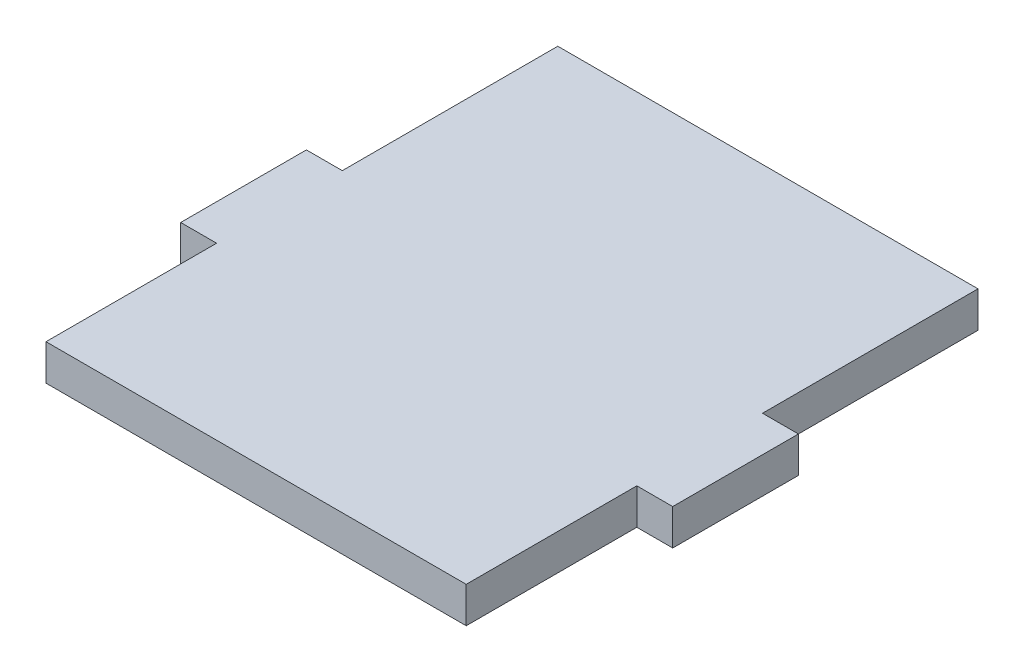
SolidWorks part; units mm, degrees
ref_plane "Front Plane" through (0, 0, 0) normal (0, 0, 1) x (1, 0, 0)
ref_plane "Top Plane" through (0, 0, 0) normal (0, 1, 0) x (1, 0, 0)
ref_plane "Right Plane" through (0, 0, 0) normal (1, 0, 0) x (0, 0, -1)
sketch "Sketch1" plane through (0, 0, 0) normal (0, 1, 0) x (1, 0, 0)
  line L1 (-11.7, 14.25) -> (11.7, 14.25)
  line L2 (-11.7, 14.25) -> (-11.7, -14.25)
  line L3 (-11.7, -14.25) -> (11.7, -14.25)
  line L4 (11.7, 14.25) -> (11.7, -14.25)
  line L5 (-11.7, 14.25) -> (11.7, -14.25) construction
  line L6 (-11.7, -14.25) -> (11.7, 14.25) construction
  line L7 (11.7, -4.75) -> (13.7, -4.75)
  line L8 (11.7, -4.75) -> (11.7, 2.25)
  line L9 (11.7, 2.25) -> (13.7, 2.25)
  line L10 (13.7, -4.75) -> (13.7, 2.25)
  line L11 (-11.7, 2.25) -> (-13.7, 2.25)
  line L12 (-11.7, 2.25) -> (-11.7, -4.75)
  line L13 (-11.7, -4.75) -> (-13.7, -4.75)
  line L14 (-13.7, 2.25) -> (-13.7, -4.75)
  point P0 (0, 0)
  dimension "D1" = 28.5
  dimension "D2" = 23.4
  dimension "D3" = 2
  dimension "D4" = 2
  dimension "D5" = 7
  dimension "D6" = 7
  dimension "D7" = 9.5
  dimension "D8" = 9.5
extrude "Boss-Extrude1" add sketch "Sketch1" along normal blind 2 contours L4 L1 L2 L3 | L11 L14 L13 L2 | L7 L10 L9 L4
